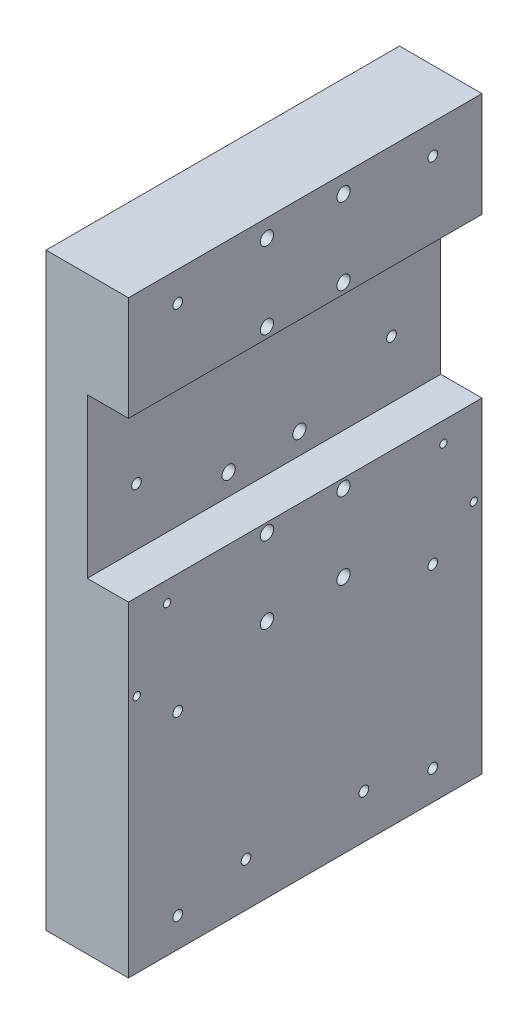
SolidWorks part; units mm, degrees
ref_plane "Front Plane" through (0, 0, 0) normal (0, 0, 1) x (1, 0, 0)
ref_plane "Top Plane" through (0, 0, 0) normal (0, 1, 0) x (1, 0, 0)
ref_plane "Right Plane" through (0, 0, 0) normal (1, 0, 0) x (0, 0, -1)
sketch "Sketch1" plane through (0, 0, 0) normal (0, 0, 1) x (1, 0, 0)
  line L0 (0, 0) -> (0, 200)
  line L1 (0, 200) -> (28, 200)
  line L2 (28, 200) -> (28, 164.5)
  line L3 (14, 164.5) -> (14, 110.5)
  line L4 (14, 164.5) -> (28, 164.5)
  line L5 (14, 110.5) -> (28, 110.5)
  line L6 (28, 110.5) -> (28, 0)
  line L7 (28, 0) -> (0, 0)
  line L8 (-49.525, 137.5) -> (95.9642, 137.5) construction
  point P12 (14, 137.5)
  dimension "D1" = 200
  dimension "D2" = 27
  dimension "D4" = 28
  dimension "D6" = 62.5
extrude "Boss-Extrude1" add sketch "Sketch1" along normal blind 120 contours L0 L1 L2 L4 L3 L5 L6 L7
sketch "Sketch2" plane through (0, 0, 0) normal (-1, 0, 0) x (0, 0, 1)
  line L0 (60, 200) -> (60, 0) construction
  line L1 (120, 200) -> (0, 200) construction
  line L2 (120, 0) -> (0, 0) construction
  line L3 (120, 200) -> (0, 200) construction
  point P6 (73, 194)
  point P7 (73, 168)
  point P8 (72, 157.7)
  point P9 (72, 117.7)
  point P10 (73, 107.4)
  point P11 (73, 81.4)
  point P12 (47, 81.4)
  point P13 (47, 107.4)
  point P14 (48, 117.7)
  point P15 (48, 157.7)
  point P16 (47, 168)
  point P17 (47, 194)
  dimension "D1" = 6
  dimension "D2" = 26
  dimension "D3" = 36.3
  dimension "D4" = 40
  dimension "D5" = 92.6
  dimension "D6" = 26
  dimension "D7" = 13
  dimension "D8" = 12
  dimension "D9" = 13
hole_wizard "CBORE for M4 SHCS4" positions "3DSketch2" profile "Sketch4" counterbore size "M4" standard "ANSI Metric" end condition through all
sketch3d "3DSketch2"
  point P0 (0, 194, 73)
  point P3 (0, 168, 73)
  point P6 (0, 157.7, 72)
  point P9 (0, 117.7, 72)
  point P12 (0, 107.4, 73)
  point P15 (0, 81.4, 73)
  point P18 (0, 81.4, 47)
  point P21 (0, 107.4, 47)
  point P24 (0, 117.7, 48)
  point P27 (0, 157.7, 48)
  point P30 (0, 168, 47)
  point P33 (0, 194, 47)
sketch "Sketch4" plane through (0, 194, 73) normal (0, 1, 0) x (0, 0, 1)
  line L0 (0, 0) -> (0, 28)
  line L1 (0, 28) -> (2.25, 28)
  line L3 (2.25, 28) -> (2.25, 4)
  line L4 (2.25, 4) -> (4, 4)
  line L5 (4, 4) -> (4, 0)
  line L7 (4, 0) -> (0, 0)
  line L11 (0, -6.35) -> (0, 107.95) construction
  dimension "Thru Hole Dia." = 4.5
  dimension "Thru Hole Depth" = 28
  dimension "C'Bore Dia." = 8
  dimension "C'Bore Depth" = 4
sketch "Sketch5" plane through (0, 0, 0) normal (-1, 0, 0) x (0, 0, 1)
  line L0 (16.7, 200) -> (16.7, 0) construction
  line L1 (120, 200) -> (0, 200) construction
  line L2 (120, 0) -> (0, 0) construction
  line L3 (60, 200) -> (60, 0) construction
  line L4 (60, 200) -> (60, 0) construction
  line L5 (103.3, 200) -> (103.3, 0) construction
  point P12 (16.7, 190)
  point P13 (103.3, 10)
  point P14 (16.7, 130)
  point P15 (16.7, 70)
  point P16 (16.7, 10)
  point P17 (103.3, 70)
  point P18 (103.3, 130)
  point P19 (103.3, 190)
  dimension "D1" = 43.3
  dimension "D2" = 10
  dimension "D3" = 4
hole_wizard "M4 Tapped Hole1" positions "3DSketch3" profile "Sketch6" tap size "M4" standard "ISO" end condition through all
sketch3d "3DSketch3"
  point P0 (0, 190, 16.7)
  point P3 (0, 130, 16.7)
  point P6 (0, 70, 16.7)
  point P9 (0, 10, 16.7)
  point P12 (0, 10, 103.3)
  point P15 (0, 70, 103.3)
  point P18 (0, 130, 103.3)
  point P21 (0, 190, 103.3)
sketch "Sketch6" plane through (0, 190, 16.7) normal (0, 1, 0) x (0, 0, 1)
  line L0 (0, 0) -> (0, 28)
  line L1 (0, 28) -> (1.65, 28)
  line L2 (1.65, 28) -> (1.65, 0)
  line L5 (1.65, 0) -> (0, 0)
  line L11 (0, -6.35) -> (0, 107.95) construction
  dimension "Thread Major Dia." = 3.3
  dimension "Thru Tap Drill Depth" = 28
ref_plane "Plane1" through (0, 0, 60) normal (0, 0, -1) x (-1, 0, 0)
sketch "Sketch7" plane through (0, 0, 0) normal (0, -1, 0) x (1, 0, 0)
  line L0 (14, 120) -> (14, 0) construction
  line L1 (28, 120) -> (0, 120) construction
  line L2 (28, 0) -> (0, 0) construction
  line L3 (28, 60) -> (0, 60) construction
  line L4 (28, 120) -> (28, 0) construction
  line L5 (0, 120) -> (0, 0) construction
  point P12 (14, 60)
  point P13 (14, 90)
  point P14 (14, 30)
  dimension "D1" = 30
hole_wizard "M5 Tapped Hole1" positions "3DSketch4" profile "Sketch8" tap size "M5" standard "ISO"
sketch3d "3DSketch4"
  point P0 (14, 0, 90)
  point P3 (14, 0, 60)
  point P6 (14, 0, 30)
sketch "Sketch8" plane through (14, 0, 90) normal (1, 0, 0) x (0, 0, -1)
  line L0 (0, 0) -> (0, 18.6618)
  line L1 (0, 18.6618) -> (2.1, 17.4)
  line L2 (2.1, 17.4) -> (2.1, 0)
  line L5 (2.1, 0) -> (0, 0)
  line L10 (0, 18.6618) -> (-2.1, 17.4) construction
  line L11 (0, -6.35) -> (0, 107.95) construction
  dimension "Tap Drill Dia." = 4.2
  dimension "Tap Drill Depth" = 17.4
  dimension "Drill Angle" = 118
sketch "Sketch9" plane through (28, 0, 0) normal (1, 0, 0) x (0, 0, -1)
  line L0 (-40.1, 23.78) -> (-40.1, 0) construction
  line L1 (-80.1, 23.78) -> (-80.1, 0) construction
  line L8 (-120, 0) -> (0, 0) construction
  line L11 (-120, 0) -> (0, 0) construction
  point P8 (-40.1, 15)
  point P9 (-80.1, 15)
  dimension "D1" = 15
hole_wizard "M4 Tapped Hole2" positions "3DSketch5" profile "Sketch10" tap size "M4" standard "ISO" end condition through all
sketch3d "3DSketch5"
  point P0 (28, 15, 80.1)
  point P3 (28, 15, 40.1)
sketch "Sketch10" plane through (28, 15, 80.1) normal (0, 1, 0) x (0, 0, -1)
  line L0 (0, 0) -> (0, 28)
  line L1 (0, 28) -> (1.65, 28)
  line L2 (1.65, 28) -> (1.65, 0)
  line L5 (1.65, 0) -> (0, 0)
  line L11 (0, -6.35) -> (0, 107.95) construction
  dimension "Thread Major Dia." = 3.3
  dimension "Thru Tap Drill Depth" = 28
sketch "Sketch16" plane through (28, 0, 0) normal (1, 0, 0) x (0, 0, -1)
  line L0 (-60, 200) -> (-60, 0) construction
  point P0 (-2.8, 81.4604)
  point P1 (-13.1, 103.6604)
  point P8 (-117.2, 81.4604)
  point P9 (-106.9, 103.6604)
hole_wizard "M3 Tapped Hole2" positions "3DSketch12" profile "Sketch18" tap size "M3" standard "ISO"
sketch3d "3DSketch12"
  point P0 (28, 103.6604, 106.9)
  point P3 (28, 81.4604, 117.2)
  point P6 (28, 103.6604, 13.1)
  point P9 (28, 81.4604, 2.8)
sketch "Sketch18" plane through (28, 103.6604, 106.9) normal (0, 1, 0) x (0, 0, -1)
  line L0 (0, 0) -> (0, 12.2511)
  line L1 (0, 12.2511) -> (1.25, 11.5)
  line L2 (1.25, 11.5) -> (1.25, 0)
  line L5 (1.25, 0) -> (0, 0)
  line L10 (0, 12.2511) -> (-1.25, 11.5) construction
  line L11 (0, -6.35) -> (0, 107.95) construction
  dimension "Tap Drill Dia." = 2.5
  dimension "Tap Drill Depth" = 11.5
  dimension "Drill Angle" = 118
